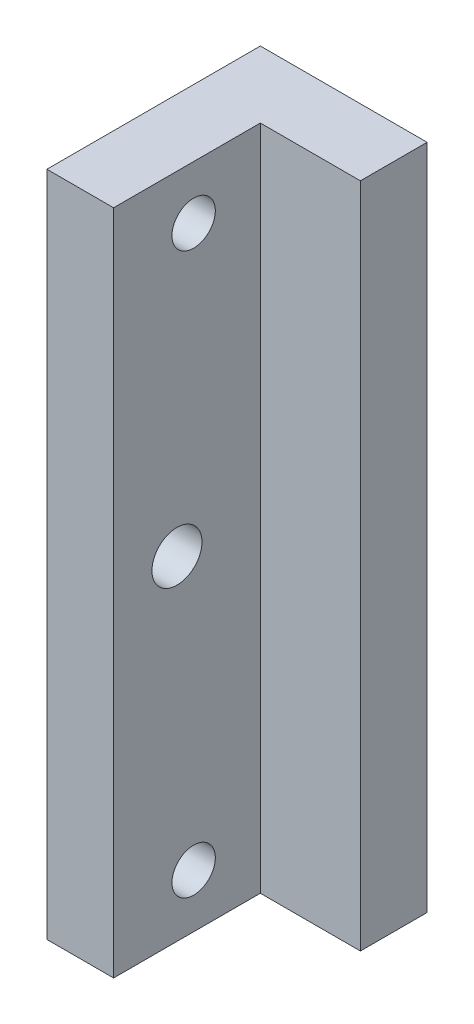
SolidWorks part; units mm, degrees
ref_plane "Front" through (0, 0, 0) normal (0, 0, 1) x (1, 0, 0)
ref_plane "Top" through (0, 0, 0) normal (0, 1, 0) x (1, 0, 0)
ref_plane "Right" through (0, 0, 0) normal (1, 0, 0) x (0, 0, -1)
sketch "Sketch1" plane through (0, 0, 0) normal (0, 1, 0) x (1, 0, 0)
  line L0 (25, 0) -> (0, 0)
  line L1 (0, 0) -> (0, -32)
  line L2 (0, -32) -> (10, -32)
  line L3 (10, -32) -> (10, -10)
  line L4 (10, -10) -> (25, -10)
  line L5 (25, -10) -> (25, 0)
  dimension "D1" = 25
  dimension "D2" = 32
  dimension "D3" = 10
extrude "Boss-Extrude1" add sketch "Sketch1" along normal mid plane 100
hole_wizard "Ø6.5 (6.5) Diameter Hole1" positions "Sketch3" profile "Sketch2" hole size "Ø6.5" standard "ISO" end condition through all
sketch "Sketch3" plane through (0, 0, 0) normal (-1, 0, 0) x (0, 0, 1)
  line L0 (0, 0) -> (32, 0) construction
  line L1 (0, 50) -> (0, -50) construction
  line L2 (32, 50) -> (32, -50) construction
  point P0 (20, -42)
  point P1 (20, 42)
  dimension "D1" = 84
  dimension "D2" = 20
sketch "Sketch2" plane through (0, -42, 20) normal (0, 1, 0) x (0, 0, 1)
  line L0 (0, 0) -> (0, 25)
  line L1 (0, 25) -> (3.25, 25)
  line L2 (3.25, 25) -> (3.25, 0)
  line L5 (3.25, 0) -> (0, 0)
  line L11 (0, -6.35) -> (0, 107.95) construction
  dimension "Thru Hole Dia." = 6.5
  dimension "Thru Hole Depth" = 25
sketch "Sketch4" plane through (0, 0, 0) normal (-1, 0, 0) x (0, 0, 1)
  line L0 (0, 50) -> (0, -50) construction
  circle A0 centre (22.5, 0) radius 3.75
  dimension "D1" = 7.5
  dimension "D2" = 22.5
extrude "Cut-Extrude1" cut sketch "Sketch4" against normal through all
